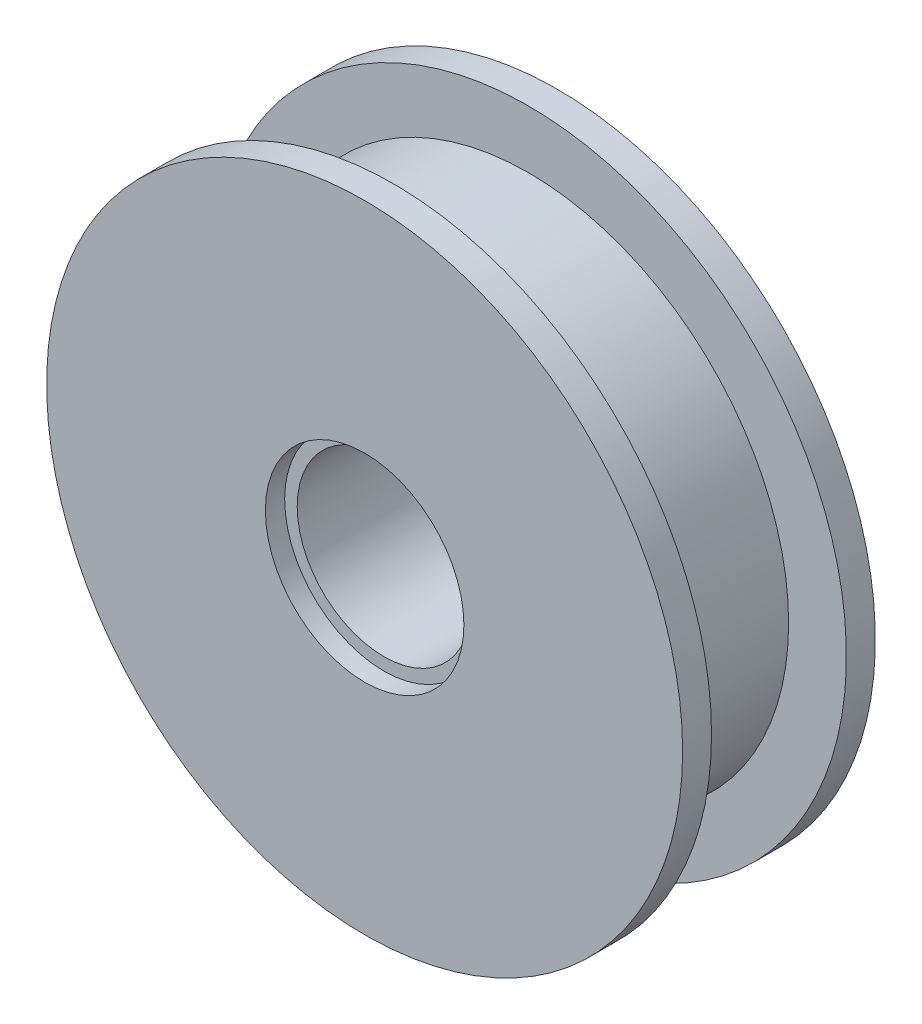
SolidWorks part; units mm, degrees
ref_plane "Front Plane" through (0, 0, 0) normal (0, 0, 1) x (1, 0, 0)
ref_plane "Top Plane" through (0, 0, 0) normal (0, 1, 0) x (1, 0, 0)
ref_plane "Right Plane" through (0, 0, 0) normal (1, 0, 0) x (0, 0, -1)
sketch "Sketch1" plane through (0, 0, 0) normal (0, 0, 1) x (1, 0, 0)
  circle A0 centre (0, 0) radius 13.5
  circle A1 centre (0, 0) radius 4.5
  dimension "D1" = 27
  dimension "D2" = 9
extrude "Boss-Extrude1" add sketch "Sketch1" along normal blind 10
sketch "Sketch2" plane through (0, 0, 10) normal (0, 0, 1) x (1, 0, 0)
  circle A0 centre (0, 0) radius 5.15
  dimension "D1" = 10.3
extrude "Cut-Extrude1" cut sketch "Sketch2" against normal blind 1
sketch "Sketch3" plane through (0, 0, 0) normal (0, 0, -1) x (-1, 0, 0)
  circle A0 centre (0, 0) radius 5.15
  circle A1 centre (0, 0) radius 5.15 construction
extrude "Cut-Extrude2" cut sketch "Sketch3" against normal blind 1
sketch "Sketch4" plane through (0, 0, 0) normal (0, 0, -1) x (-1, 0, 0)
  circle A0 centre (0, 0) radius 16.5
  circle A1 centre (0, 0) radius 5.15
  dimension "D1" = 33
extrude "Boss-Extrude2" add sketch "Sketch4" against normal blind 1.5
sketch "Sketch5" plane through (0, 0, 10) normal (0, 0, 1) x (1, 0, 0)
  circle A0 centre (0, 0) radius 16.5
  circle A1 centre (0, 0) radius 5.15
  circle A2 centre (0, 0) radius 5.15 construction
  circle A3 centre (0, 0) radius 16.5 construction
extrude "Boss-Extrude3" add sketch "Sketch5" against normal blind 1.5
